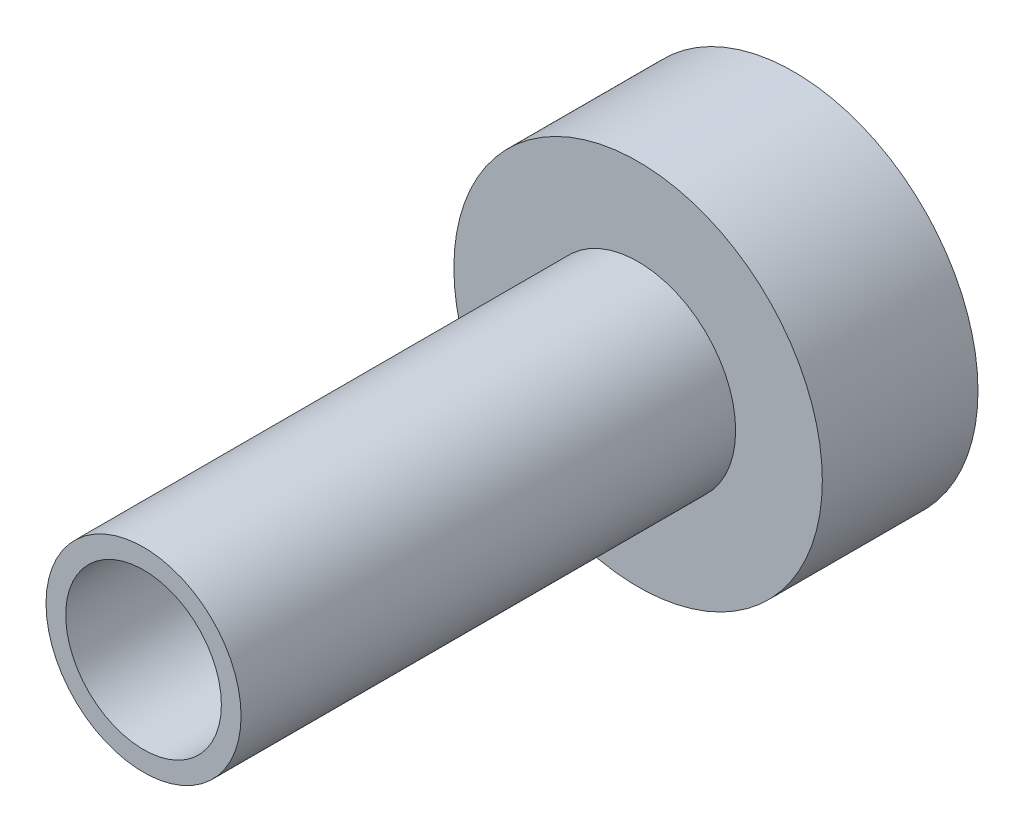
SolidWorks part; units mm, degrees
ref_plane "Front Plane" through (0, 0, 0) normal (0, 0, 1) x (1, 0, 0)
ref_plane "Top Plane" through (0, 0, 0) normal (0, 1, 0) x (1, 0, 0)
ref_plane "Right Plane" through (0, 0, 0) normal (1, 0, 0) x (0, 0, -1)
sketch "Sketch1" plane through (0, 0, 0) normal (0, 0, 1) x (1, 0, 0)
  circle A0 centre (0, 0) radius 9.35
  circle A1 centre (0, 0) radius 3.95
  dimension "D1" = 18.7
  dimension "D2" = 7.9
extrude "Boss-Extrude1" add sketch "Sketch1" along normal blind 33
sketch "Sketch2" plane through (0, 0, 33) normal (0, 0, 1) x (1, 0, 0)
  circle A0 centre (0, 0) radius 4.95
  circle A1 centre (0, 0) radius 9.35
  circle A2 centre (0, 0) radius 9.35 construction
  dimension "D1" = 9.9
extrude "Cut-Extrude1" cut sketch "Sketch2" against normal blind 25.1
